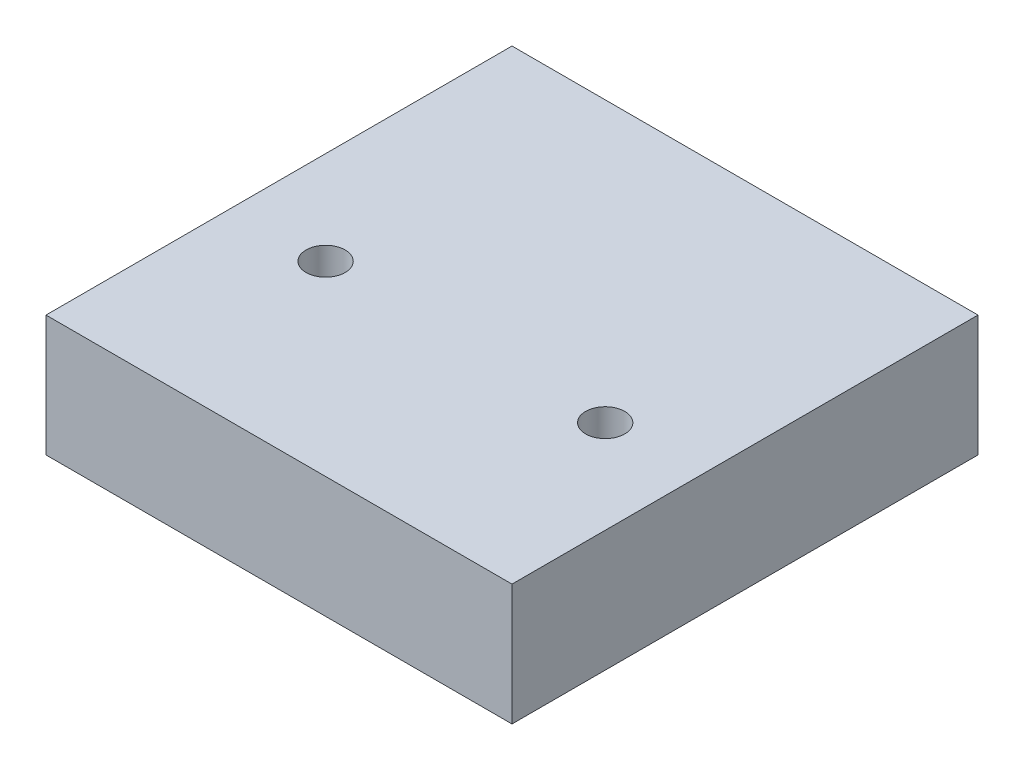
SolidWorks part; units mm, degrees
ref_plane "前视基准面" through (0, 0, 0) normal (0, 0, 1) x (1, 0, 0)
ref_plane "上视基准面" through (0, 0, 0) normal (0, 1, 0) x (1, 0, 0)
ref_plane "右视基准面" through (0, 0, 0) normal (1, 0, 0) x (0, 0, -1)
sketch "草图1" plane through (0, 0, 0) normal (0, 1, 0) x (1, 0, 0)
  line L1 (-25, -25) -> (25, -25)
  line L2 (-25, -25) -> (-25, 25)
  line L3 (-25, 25) -> (25, 25)
  line L4 (25, -25) -> (25, 25)
  line L5 (-25, -25) -> (25, 25) construction
  line L6 (-25, 25) -> (25, -25) construction
  point P0 (0, 0)
  dimension "D1" = 50
  dimension "D2" = 50
extrude "凸台-拉伸1" add sketch "草图1" along normal blind 13
sketch "草图3" plane through (0, 13, 0) normal (0, 1, 0) x (1, 0, 0)
  line L0 (-25, -5) -> (25, -5) construction
  line L1 (-25, 25) -> (-25, -25) construction
  line L2 (25, -25) -> (25, 25) construction
  line L4 (-25, -25) -> (25, -25) construction
  circle A0 centre (-15, -5) radius 2.1
  circle A1 centre (15, -5) radius 2.1
  dimension "D2" = 4.2
  dimension "D3" = 4.2
  dimension "D1" = 20
  dimension "D4" = 15
  dimension "D5" = 15
extrude "切除-拉伸1" cut sketch "草图3" against normal up to next
